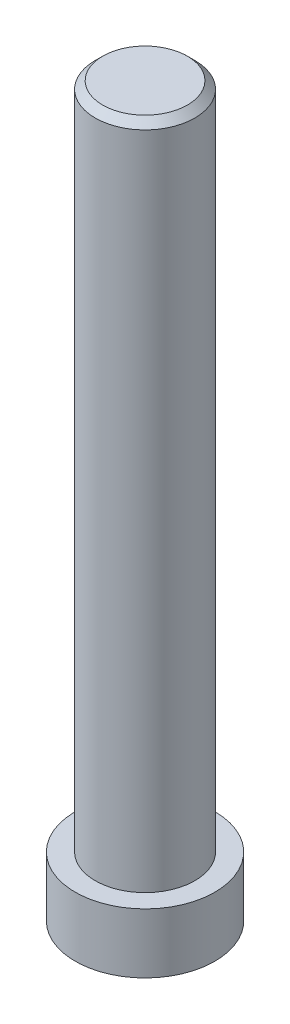
SolidWorks part; units mm, degrees
material "AISI 4340 Steel, annealed"
ref_plane "Front Plane" through (0, 0, 0) normal (0, 0, 1) x (1, 0, 0)
ref_plane "Top Plane" through (0, 0, 0) normal (0, 1, 0) x (1, 0, 0)
ref_plane "Right Plane" through (0, 0, 0) normal (1, 0, 0) x (0, 0, -1)
sketch "Sketch1" plane through (0, 0, 0) normal (0, 1, 0) x (1, 0, 0)
  circle A0 centre (0, 0) radius 5
  dimension "D1" = 10
extrude "Boss-Extrude1" add sketch "Sketch1" along normal blind 67
cosmetic thread "Cosmetic Thread1" parameters "D1"=10, "D2"=8.344
chamfer "Chamfer1" distance 0.75 angle 45 1 edges at (0, 67, 5)
sketch "Sketch2" plane through (0, 0, 0) normal (0, -1, 0) x (1, 0, 0)
  circle A0 centre (0, 0) radius 7
  dimension "D1" = 14
extrude "Boss-Extrude2" add sketch "Sketch2" along normal blind 6
sketch "Sketch3" plane through (0, -6, 0) normal (0, -1, 0) x (1, 0, 0)
  line L1 (0, 3.0022) -> (-2.6, 1.5011)
  line L2 (-2.6, 1.5011) -> (-2.6, -1.5011)
  line L3 (-2.6, -1.5011) -> (0, -3.0022)
  line L4 (0, -3.0022) -> (2.6, -1.5011)
  line L5 (2.6, -1.5011) -> (2.6, 1.5011)
  line L6 (2.6, 1.5011) -> (0, 3.0022)
  circle A0 centre (0, 0) radius 2.6 construction
  dimension "D1" = 5.2
extrude "Cut-Extrude1" cut sketch "Sketch3" against normal blind 3.8
